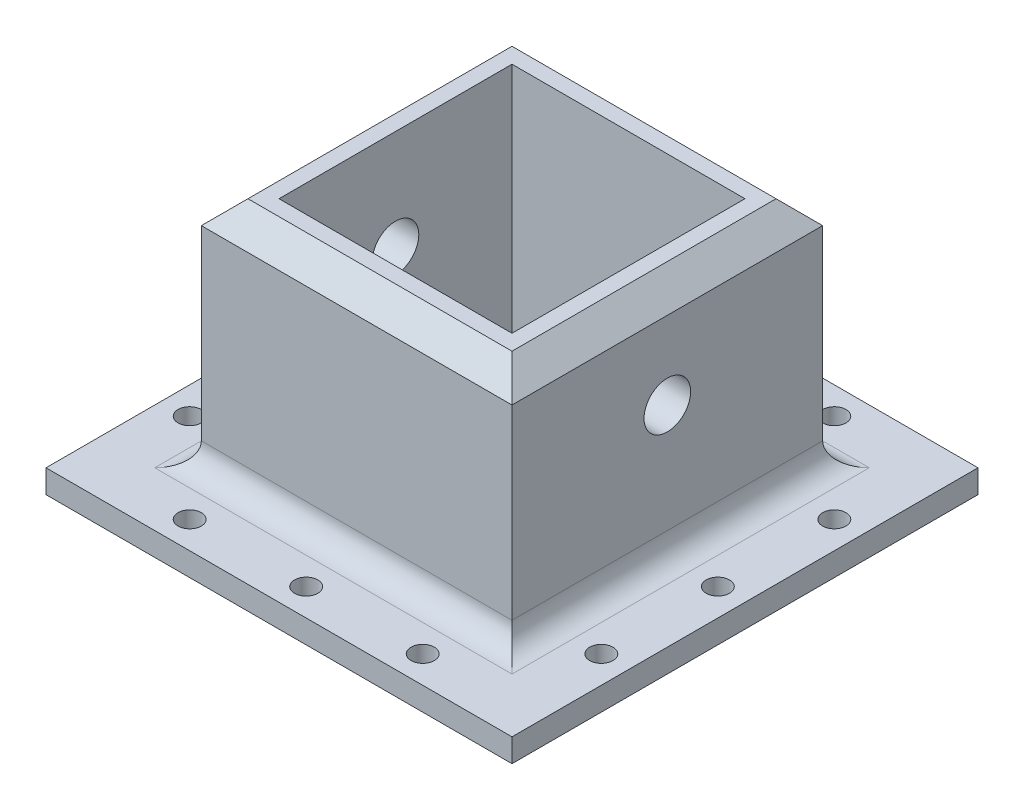
SolidWorks part; units mm, degrees
ref_plane "Alzado" through (0, 0, 0) normal (0, 0, 1) x (1, 0, 0)
ref_plane "Planta" through (0, 0, 0) normal (0, 1, 0) x (1, 0, 0)
ref_plane "Vista lateral" through (0, 0, 0) normal (1, 0, 0) x (0, 0, -1)
sketch "Croquis1" plane through (0, 0, 0) normal (0, 1, 0) x (1, 0, 0)
  line L1 (-30, -30) -> (30, -30)
  line L2 (-30, -30) -> (-30, 30)
  line L3 (-30, 30) -> (30, 30)
  line L4 (30, -30) -> (30, 30)
  line L5 (-30, -30) -> (30, 30) construction
  line L6 (-30, 30) -> (30, -30) construction
  point P0 (0, 0)
  dimension "D1" = 60
extrude "Saliente-Extruir1" add sketch "Croquis1" along normal blind 3
sketch "Croquis2" plane through (0, 3, 0) normal (0, 1, 0) x (1, 0, 0)
  line L0 (-20, -20) -> (-20, 20)
  line L1 (-15, -15) -> (15, -15)
  line L2 (-15, -15) -> (-15, 15)
  line L3 (-15, 15) -> (15, 15)
  line L4 (15, -15) -> (15, 15)
  line L5 (-15, -15) -> (15, 15) construction
  line L6 (-15, 15) -> (15, -15) construction
  line L7 (-20, 20) -> (20, 20)
  line L8 (20, -20) -> (20, 20)
  line L9 (-20, -20) -> (20, -20)
  point P0 (0, 0)
  dimension "D1" = 30
  dimension "D2" = 5
extrude "Saliente-Extruir2" add sketch "Croquis2" along normal blind 30
chamfer "Chaflán1" distance 3 angle 45 4 edges at (-20, 33, 0) (0, 33, -20) (20, 33, 0) (0, 33, 20)
fillet "Redondeo1" radius 3 4 edges at (20, 3, 0) (0, 3, 20) (-20, 3, 0) (0, 3, -20)
sketch "Croquis3" plane through (0, 3, 0) normal (0, 1, 0) x (1, 0, 0)
  line L0 (0, 26.5) -> (0, 0) construction
  circle A0 centre (0, 26.5) radius 1.5
  circle A1 centre (15, 26.5) radius 1.5
  circle A2 centre (-15, 26.5) radius 1.5
  circle A3 centre (26.5, 15) radius 1.5
  circle A4 centre (26.5, 0) radius 1.5
  circle A5 centre (26.5, -15) radius 1.5
  circle A6 centre (15, -26.5) radius 1.5
  circle A7 centre (0, -26.5) radius 1.5
  circle A8 centre (-15, -26.5) radius 1.5
  circle A9 centre (-26.5, -15) radius 1.5
  circle A10 centre (-26.5, 0) radius 1.5
  circle A11 centre (-26.5, 15) radius 1.5
  point P29 (0, 0)
  dimension "D1" = 3
  dimension "D3" = 15
  dimension "D2" = 26.5
  dimension "D4" = 4
extrude "Cortar-Extruir1" cut sketch "Croquis3" against normal blind 30
sketch "Croquis4" plane through (0, 0, 0) normal (1, 0, 0) x (0, 0, -1)
  circle A0 centre (0, 20) radius 3
  point P2 (0, 0)
  dimension "D1" = 20
  dimension "D2" = 6
extrude "Cortar-Extruir2" cut sketch "Croquis4" against normal through all both and the other way through all
